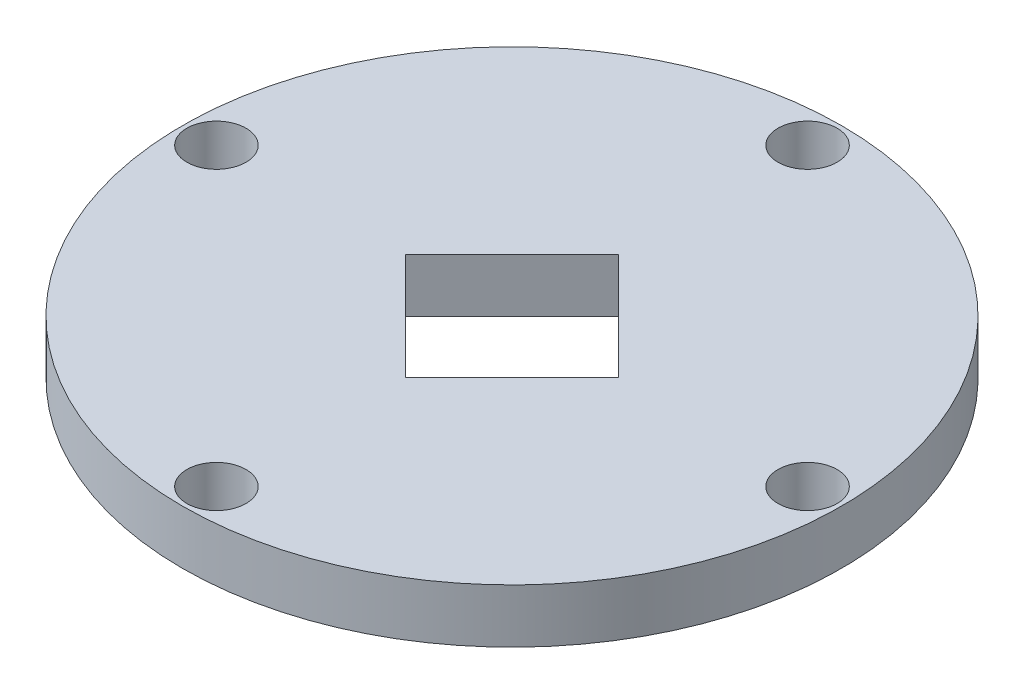
SolidWorks part; units mm, degrees
ref_plane "Front" through (0, 0, 0) normal (0, 0, 1) x (1, 0, 0)
ref_plane "Top" through (0, 0, 0) normal (0, 1, 0) x (1, 0, 0)
ref_plane "Right" through (0, 0, 0) normal (1, 0, 0) x (0, 0, -1)
sketch "Sketch1" plane through (0, 0, 0) normal (0, 1, 0) x (1, 0, 0)
  line L0 (-7.2125, 0) -> (0, -7.2125)
  line L1 (-5.1, -5.1) -> (5.1, -5.1)
  line L2 (-5.1, -5.1) -> (-5.1, 5.1)
  line L3 (-5.1, 5.1) -> (5.1, 5.1)
  line L4 (5.1, -5.1) -> (5.1, 5.1)
  line L5 (-5.1, -5.1) -> (5.1, 5.1) construction
  line L6 (-5.1, 5.1) -> (5.1, -5.1) construction
  line L7 (-7.2125, 0) -> (0, 7.2125)
  line L8 (0, 7.2125) -> (7.2125, 0)
  line L9 (0, -7.2125) -> (7.2125, 0)
  line L10 (-7.2125, 0) -> (7.2125, 0) construction
  line L11 (0, 7.2125) -> (0, -7.2125) construction
  circle A1 centre (0, 0) radius 22.3005
  point P14 (0, 0)
  dimension "D1" = 10.2
  dimension "D2" = 10.2
  dimension "D3" = 2
extrude "Boss-Extrude1" add sketch "Sketch1" along normal blind 3.65 contours L2 L7 L3 | L2 L1 L0 | L9 L1 L4 | L3 L8 L4 | A1 L9 L0 L1 L2 L7 L3 L8 L4
sketch "Sketch2" plane through (0, 3.65, 0) normal (0, 1, 0) x (1, 0, 0)
  line L0 (0, 0) -> (0, 20)
  circle A0 centre (0, 20) radius 2
  circle A1 centre (20, 0) radius 2
  circle A2 centre (0, -20) radius 2
  circle A3 centre (-20, 0) radius 2
  point P13 (0, 0)
  dimension "D2" = 4
  dimension "D1" = 20
extrude "Cut-Extrude1" cut sketch "Sketch2" against normal through all
